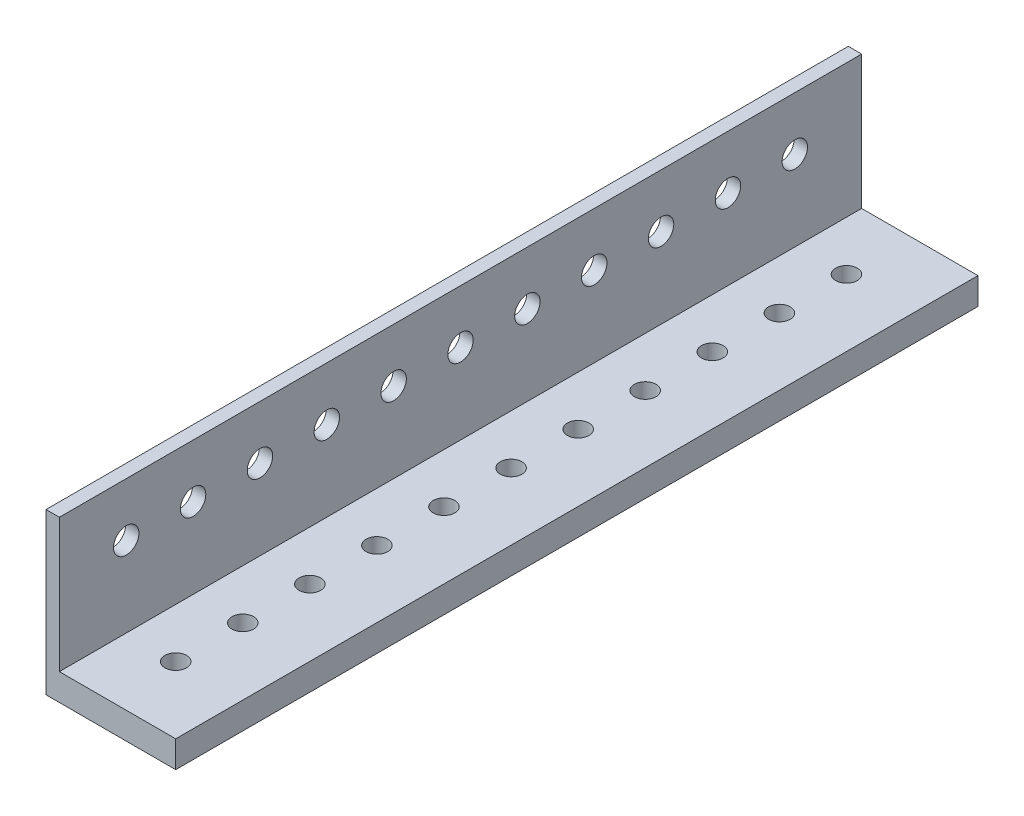
SolidWorks part; units mm, degrees
ref_plane "Front Plane" through (0, 0, 0) normal (0, 0, 1) x (1, 0, 0)
ref_plane "Top Plane" through (0, 0, 0) normal (0, 1, 0) x (1, 0, 0)
ref_plane "Right Plane" through (0, 0, 0) normal (1, 0, 0) x (0, 0, -1)
sketch "Sketch1" plane through (0, 0, 0) normal (1, 0, 0) x (0, 0, -1)
  line L0 (1.495, 4.8503) -> (1.495, -15.4697) construction
  line L1 (-11.205, 15.0103) -> (141.195, 15.0103)
  line L2 (-11.205, 15.0103) -> (-11.205, -15.4697)
  line L3 (-11.205, -15.4697) -> (141.195, -15.4697)
  line L4 (141.195, 15.0103) -> (141.195, -15.4697)
  line L5 (1.495, 4.8503) -> (-11.205, 4.8503) construction
  circle A0 centre (1.495, 4.8503) radius 2.413
  circle A1 centre (14.195, 4.8503) radius 2.413
  circle A2 centre (26.895, 4.8503) radius 2.413
  circle A3 centre (39.595, 4.8503) radius 2.413
  circle A4 centre (52.295, 4.8503) radius 2.413
  circle A5 centre (64.995, 4.8503) radius 2.413
  circle A6 centre (77.695, 4.8503) radius 2.413
  circle A7 centre (90.395, 4.8503) radius 2.413
  circle A8 centre (103.095, 4.8503) radius 2.413
  circle A9 centre (115.795, 4.8503) radius 2.413
  circle A10 centre (128.495, 4.8503) radius 2.413
  dimension "D3" = 4.826
  dimension "D4" = 20.32
  dimension "D5" = 12.7
  dimension "D1" = 30.48
  dimension "D2" = 152.4
  dimension "D6" = 11
extrude "Boss-Extrude1" add sketch "Sketch1" along normal blind 2.54
sketch "Sketch2" plane through (2.54, 0, 0) normal (1, 0, 0) x (0, 0, -1)
  line L0 (141.195, -15.4697) -> (141.195, 15.0103) construction
  line L1 (-11.205, -15.4697) -> (141.195, -15.4697)
  line L2 (-11.205, -15.4697) -> (-11.205, -10.3897)
  line L3 (-11.205, -10.3897) -> (141.195, -10.3897)
  line L4 (141.195, -15.4697) -> (141.195, -10.3897)
  dimension "D1" = 5.08
extrude "Boss-Extrude2" add sketch "Sketch2" along normal blind 22.098
sketch "Sketch3" plane through (0, -10.3897, 0) normal (0, 1, 0) x (1, 0, 0)
  line L0 (11.938, 1.495) -> (24.638, 1.495) construction
  line L1 (11.938, 128.9064) -> (11.938, 141.195) construction
  line L2 (11.938, 1.495) -> (11.938, -11.205) construction
  line L3 (24.638, -11.205) -> (2.54, -11.205) construction
  line L4 (24.638, 141.195) -> (24.638, -11.205) construction
  line L5 (24.638, 141.195) -> (2.54, 141.195) construction
  line L6 (11.938, 128.9064) -> (11.938, 116.1653) construction
  line L7 (11.938, 116.1653) -> (11.938, 103.4241) construction
  line L8 (11.938, 103.4241) -> (11.938, 90.683) construction
  line L9 (11.938, 90.683) -> (11.938, 77.9418) construction
  line L10 (11.938, 77.9418) -> (11.938, 65.2007) construction
  line L11 (11.938, 65.2007) -> (11.938, 52.4596) construction
  line L12 (11.938, 52.4596) -> (11.938, 39.7184) construction
  line L13 (11.938, 39.7184) -> (11.938, 26.9773) construction
  line L14 (11.938, 26.9773) -> (11.938, 14.2361) construction
  line L15 (11.938, 14.2361) -> (11.938, 1.495) construction
  circle A0 centre (11.938, 1.495) radius 2.0545
  circle A1 centre (11.938, 14.2361) radius 2.0545
  circle A2 centre (11.938, 26.9773) radius 2.0545
  circle A3 centre (11.938, 39.7184) radius 2.0545
  circle A4 centre (11.938, 52.4596) radius 2.0545
  circle A5 centre (11.938, 65.2007) radius 2.0545
  circle A6 centre (11.938, 77.9418) radius 2.0545
  circle A7 centre (11.938, 90.683) radius 2.0545
  circle A8 centre (11.938, 103.4241) radius 2.0545
  circle A9 centre (11.938, 116.1653) radius 2.0545
  circle A10 centre (11.938, 128.9064) radius 2.0545
  dimension "D1" = 12.7
  dimension "D2" = 12.7
extrude "Cut-Extrude1" cut sketch "Sketch3" against normal through all
ref_plane "Plane3" through (2.54, -10.3897, -141.195) normal (0, 0, 1) x (1, 0, 0)
equation "\"D1@Boss-Extrude2\"=1.00in-.13"
